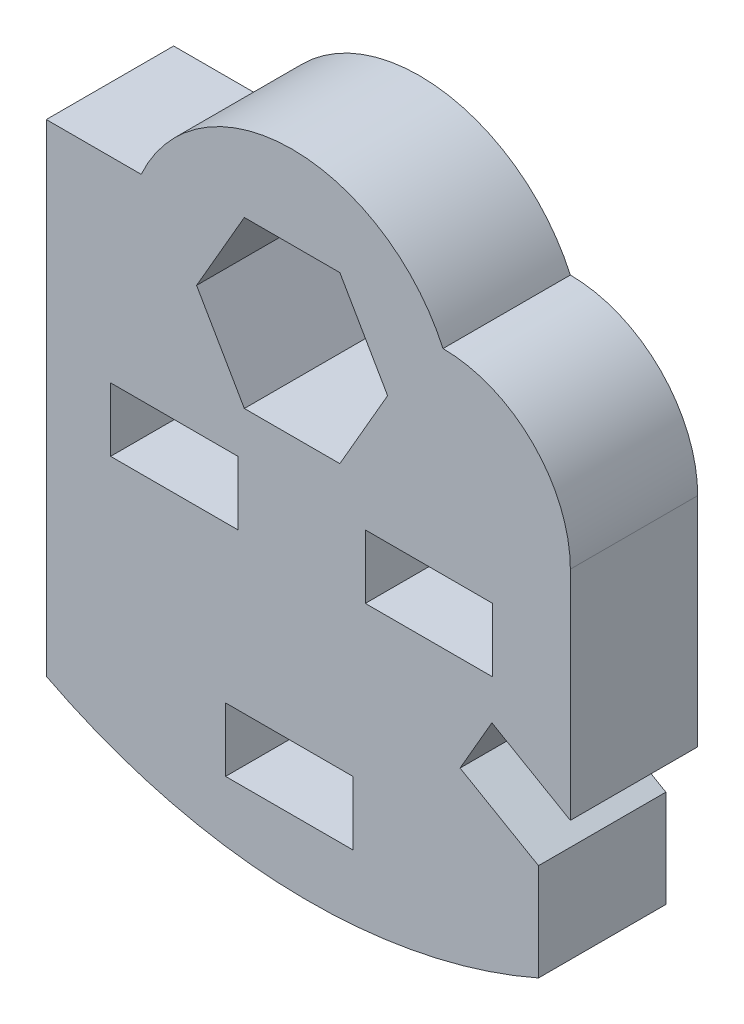
SolidWorks part; units mm, degrees
ref_plane "Front Plane" through (0, 0, 0) normal (0, 0, 1) x (1, 0, 0)
ref_plane "Top Plane" through (0, 0, 0) normal (0, 1, 0) x (1, 0, 0)
ref_plane "Right Plane" through (0, 0, 0) normal (1, 0, 0) x (0, 0, -1)
sketch "Sketch1" plane through (0, 0, 0) normal (0, 0, 1) x (1, 0, 0)
  line L0 (14.4756, 6) -> (15.4756, 7.7321)
  line L1 (3.5, 8.9911) -> (3.5, 10.9911)
  line L2 (7.1111, 2.0911) -> (11.1111, 2.0911)
  line L3 (1.48, 17.1426) -> (1.48, 2)
  line L4 (17.9397, 13.1426) -> (17.9397, 6.3094)
  line L5 (4.4603, 17.1426) -> (1.48, 17.1426)
  line L6 (11.1111, 2.0911) -> (11.1111, 4.0911)
  line L7 (16.9397, 4.5774) -> (16.9397, 1.522)
  line L8 (7.5, 8.9911) -> (7.5, 10.9911)
  line L9 (3.5, 8.9911) -> (7.5, 8.9911)
  line L10 (15.4756, 7.7321) -> (17.9397, 6.3094)
  line L11 (3.5, 10.9911) -> (7.5, 10.9911)
  line L12 (14.4756, 6) -> (16.9397, 4.5774)
  line L13 (11.5, 8.9911) -> (11.5, 10.9911)
  line L14 (11.5, 8.9911) -> (15.5, 8.9911)
  line L15 (15.5, 8.9911) -> (15.5, 10.9911)
  line L16 (11.5, 10.9911) -> (15.5, 10.9911)
  line L17 (7.1111, 2.0911) -> (7.1111, 4.0911)
  line L18 (7.1111, 4.0911) -> (11.1111, 4.0911)
  line L20 (6.2, 14.9911) -> (7.7, 12.393)
  line L21 (7.7, 12.393) -> (10.7, 12.393)
  line L22 (10.7, 12.393) -> (12.2, 14.9911)
  line L23 (12.2, 14.9911) -> (10.7, 17.5892)
  line L24 (10.7, 17.5892) -> (7.7, 17.5892)
  line L25 (7.7, 17.5892) -> (6.2, 14.9911)
  arc A0 (17.9397, 13.1426) -> (13.9397, 17.1426) centre (13.9397, 13.1426) ccw
  arc A1 (1.48, 2) -> (16.9397, 1.522) centre (9.7098, 17.9326) ccw
  arc A3 (13.9397, 17.1426) -> (4.4603, 17.1426) centre (9.2, 14.9926) ccw
  dimension "D1" = 4
  dimension "D2" = 2.8453
  dimension "D9" = 4
  dimension "D6" = 17.9326
  dimension "D8" = 5.2045
  dimension "D3" = 6.8332
  dimension "D4" = 2
  dimension "D5" = 3.0553
  dimension "D7" = 15.4597
  dimension "D10" = 2
  dimension "D11" = 2
  dimension "D12" = 4
  dimension "D13" = 4
  dimension "D14" = 4
  dimension "D15" = 2
extrude "Boss-Extrude1" add sketch "Sketch1" along normal blind 4
